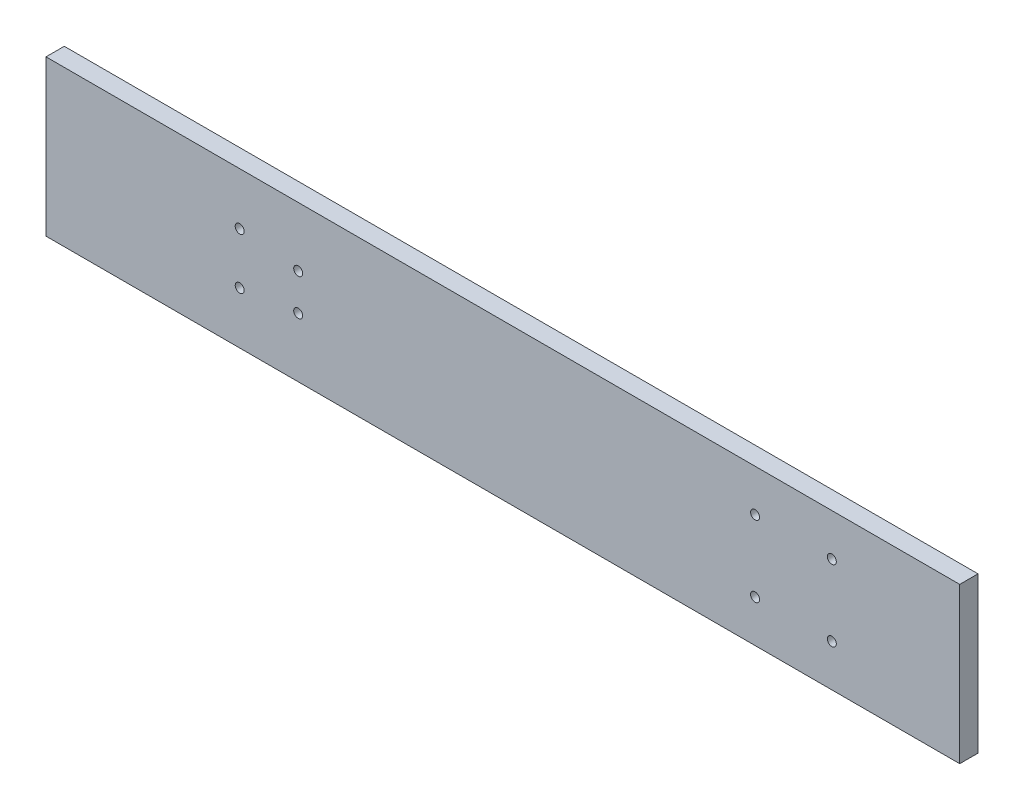
SolidWorks part; units mm, degrees
material "Oak"
ref_plane "Front Plane" through (0, 0, 0) normal (0, 0, 1) x (1, 0, 0)
ref_plane "Top Plane" through (0, 0, 0) normal (0, 1, 0) x (1, 0, 0)
ref_plane "Right Plane" through (0, 0, 0) normal (1, 0, 0) x (0, 0, -1)
sketch "Sketch1" plane through (0, 0, 0) normal (0, 0, 1) x (1, 0, 0)
  line L1 (-250, 42.5) -> (250, 42.5)
  line L2 (-250, 42.5) -> (-250, -42.5)
  line L3 (-250, -42.5) -> (250, -42.5)
  line L4 (250, 42.5) -> (250, -42.5)
  line L5 (-250, 42.5) -> (250, -42.5) construction
  line L6 (-250, -42.5) -> (250, 42.5) construction
  point P0 (0, 0)
  dimension "D1" = 500
  dimension "D2" = 85
extrude "Boss-Extrude1" add sketch "Sketch1" along normal blind 10
hole_wizard "#10 (0.1935) Diameter Hole1" positions "Sketch2" profile "Sketch3" hole size "#10" standard "ANSI Inch"
sketch "Sketch2" plane through (0, 0, 10) normal (0, 0, 1) x (1, 0, 0)
  line L0 (250, -42.5) -> (250, 42.5) construction
  line L1 (0, 0) -> (54.5869, 0) construction
  point P0 (180, 19.5)
  point P2 (180, -19.5)
  point P4 (138, -19.5)
  point P6 (138, 19.5)
  dimension "D1" = 70
  dimension "D2" = 39
  dimension "D3" = 42
  dimension "D4" = 19.5
sketch "Sketch3" plane through (180, 19.5, 10) normal (1, 0, 0) x (0, -1, 0)
  line L0 (0, 0) -> (0, 6.4766)
  line L1 (0, 6.4766) -> (2.4574, 5)
  line L2 (2.4574, 5) -> (2.4574, 0)
  line L5 (2.4574, 0) -> (0, 0)
  line L10 (0, 6.4766) -> (-2.4575, 5) construction
  line L11 (0, -6.35) -> (0, 107.95) construction
  dimension "Hole Dia." = 4.9149
  dimension "Hole Depth" = 5
  dimension "Drill Angle" = 118
hole_wizard "#10 (0.1935) Diameter Hole2" positions "Sketch4" profile "Sketch5" hole size "#10" standard "ANSI Inch"
sketch "Sketch4" plane through (0, 0, 10) normal (0, 0, 1) x (1, 0, 0)
  point P0 (-144, 14)
  point P2 (-112, 10)
  point P4 (-112, -10)
  point P6 (-144, -14)
  dimension "D1" = 32
  dimension "D2" = 28
  dimension "D3" = 10
  dimension "D4" = 250
  dimension "D5" = 20
  dimension "D6" = 4
sketch "Sketch5" plane through (-144, 14, 10) normal (1, 0, 0) x (0, -1, 0)
  line L0 (0, 0) -> (0, 6.4766)
  line L1 (0, 6.4766) -> (2.4574, 5)
  line L2 (2.4574, 5) -> (2.4574, 0)
  line L5 (2.4574, 0) -> (0, 0)
  line L10 (0, 6.4766) -> (-2.4574, 5) construction
  line L11 (0, -6.35) -> (0, 107.95) construction
  dimension "Hole Dia." = 4.9149
  dimension "Hole Depth" = 5
  dimension "Drill Angle" = 118
